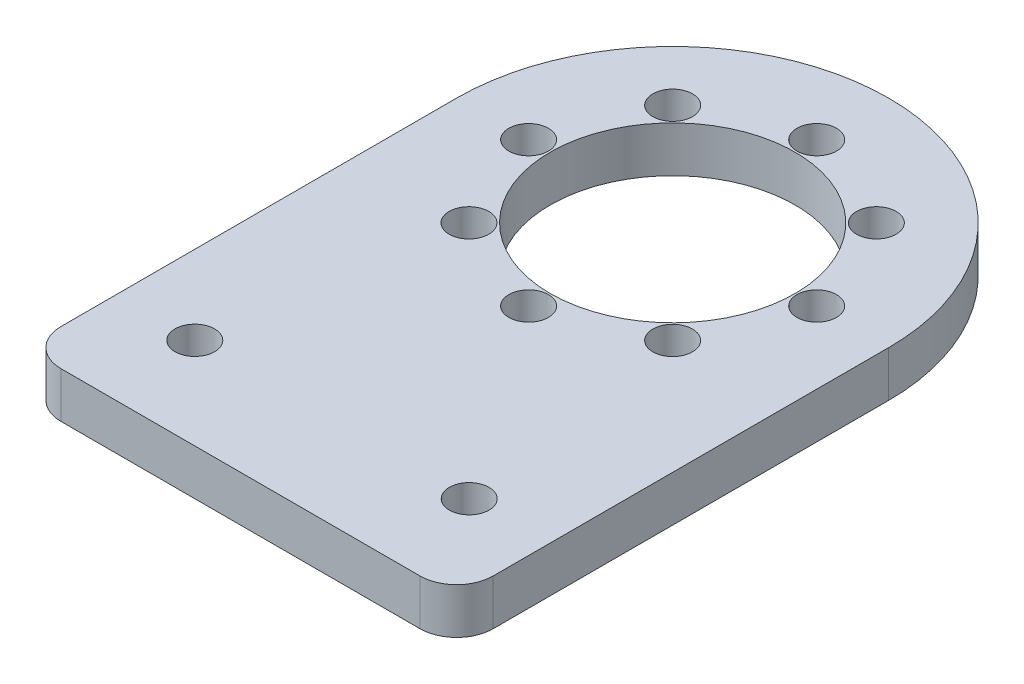
SolidWorks part; units mm, degrees
ref_plane "Front Plane" through (0, 0, 0) normal (0, 0, 1) x (1, 0, 0)
ref_plane "Top Plane" through (0, 0, 0) normal (0, 1, 0) x (1, 0, 0)
ref_plane "Right Plane" through (0, 0, 0) normal (1, 0, 0) x (0, 0, -1)
sketch "Sketch1" plane through (0, 0, 0) normal (0, 1, 0) x (1, 0, 0)
  line L0 (30, 60) -> (30, 0) construction
  line L1 (0, 0) -> (60, 0)
  line L2 (0, 0) -> (0, 60)
  line L4 (60, 0) -> (60, 60)
  circle A0 centre (30, 60) radius 30
  point P1 (30, 90)
  point P5 (0, 60)
  point P8 (60, 60)
  dimension "D2" = 90
  dimension "D1" = 60
extrude "Boss-Extrude1" add sketch "Sketch1" along normal blind 6.35
sketch "Sketch2" plane through (0, 6.35, 0) normal (0, 1, 0) x (1, 0, 0)
  line L0 (0, 60) -> (60, 60) construction
  circle A0 centre (30, 60) radius 17
  dimension "D1" = 34
extrude "Cut-Extrude1" cut sketch "Sketch2" against normal through all
hole_wizard "M5 Clearance Hole1" positions "Sketch5" profile "Sketch3" hole size "M5" standard "ANSI Metric" end condition through all
sketch "Sketch5" plane through (0, 6.35, 0) normal (0, 1, 0) x (-1, 0, 0)
  line L0 (-15.8579, -74.1421) -> (-44.1421, -45.8579) construction
  line L2 (-44.1421, -74.1421) -> (-15.8579, -45.8579) construction
  line L4 (-30, -60) -> (-30, -73.9715) construction
  circle A0 centre (-30, -60) radius 17 construction
  circle A1 centre (-30, -60) radius 17
  circle A2 centre (-30, -60) radius 20
  point P8 (-15.8579, -74.1421)
  point P9 (-44.1421, -45.8579)
  point P11 (-44.1421, -74.1421)
  point P13 (-15.8579, -45.8579)
  point P23 (-30, -80)
  point P25 (-50, -60)
  point P27 (-30, -40)
  point P29 (-10, -60)
  dimension "D2" = 40
  dimension "D1" = 45
sketch "Sketch3" plane through (15.8579, 6.35, -74.1421) normal (1, 0, 0) x (0, 0, 1)
  line L0 (0, 0) -> (0, 6.35)
  line L1 (0, 6.35) -> (2.75, 6.35)
  line L2 (2.75, 6.35) -> (2.75, 0)
  line L5 (2.75, 0) -> (0, 0)
  line L11 (0, -6.35) -> (0, 107.95) construction
  dimension "Thru Hole Dia." = 5.5
  dimension "Thru Hole Depth" = 6.35
hole_wizard "M5 Clearance Hole2" positions "Sketch7" profile "Sketch6" hole size "M5" standard "ANSI Metric" end condition through all
sketch "Sketch7" plane through (0, 6.35, 0) normal (0, 1, 0) x (-1, 0, 0)
  line L0 (-30, 0) -> (-30, -21.3071) construction
  line L1 (0, 0) -> (-60, 0) construction
  line L3 (0, -12.7) -> (-60, -12.7) construction
  line L4 (0, 0) -> (0, -60) construction
  line L5 (-60, 0) -> (-60, -60) construction
  point P13 (-10.95, -12.7)
  point P15 (-49.05, -12.7)
  dimension "D1" = 12.7
  dimension "D2" = 38.1
sketch "Sketch6" plane through (10.95, 6.35, -12.7) normal (1, 0, 0) x (0, 0, 1)
  line L0 (0, 0) -> (0, 6.35)
  line L1 (0, 6.35) -> (2.75, 6.35)
  line L2 (2.75, 6.35) -> (2.75, 0)
  line L5 (2.75, 0) -> (0, 0)
  line L11 (0, -6.35) -> (0, 107.95) construction
  dimension "Thru Hole Dia." = 5.5
  dimension "Thru Hole Depth" = 6.35
fillet "Fillet1" radius 5.08 2 edges at (60, 3.175, 0) (0, 3.175, 0)
